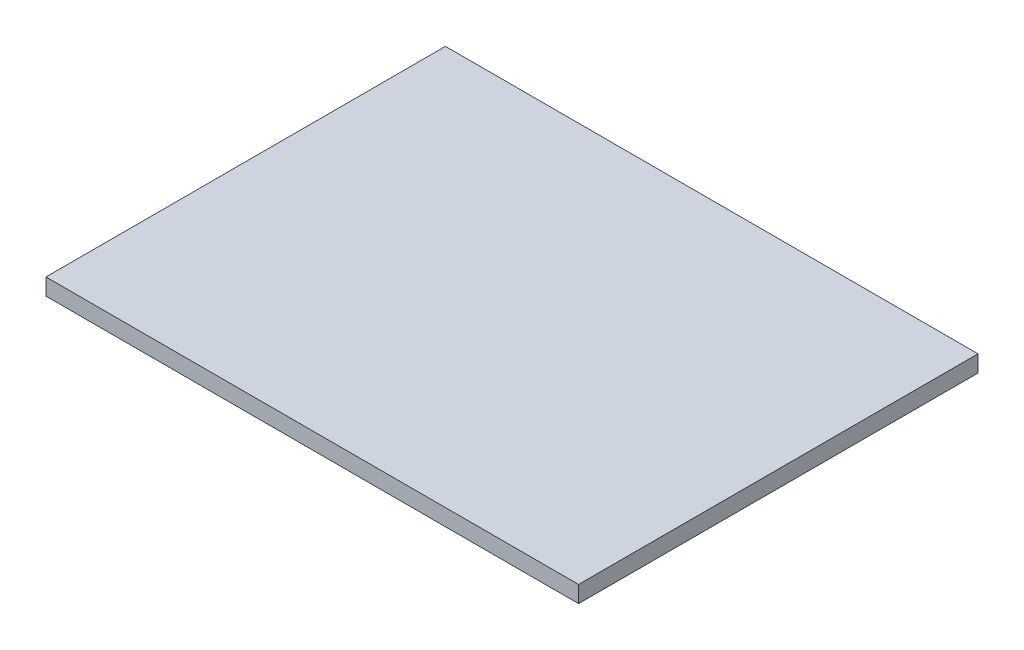
SolidWorks part; units mm, degrees
material "Brass"
ref_plane "Front Plane" through (0, 0, 0) normal (0, 0, 1) x (1, 0, 0)
ref_plane "Top Plane" through (0, 0, 0) normal (0, 1, 0) x (1, 0, 0)
ref_plane "Right Plane" through (0, 0, 0) normal (1, 0, 0) x (0, 0, -1)
sketch "Sketch1" plane through (0, 0, 0) normal (0, 1, 0) x (1, 0, 0)
  line L1 (-101.6, -76.2) -> (101.6, -76.2)
  line L2 (-101.6, -76.2) -> (-101.6, 76.2)
  line L3 (-101.6, 76.2) -> (101.6, 76.2)
  line L4 (101.6, -76.2) -> (101.6, 76.2)
  line L5 (-101.6, -76.2) -> (101.6, 76.2) construction
  line L6 (-101.6, 76.2) -> (101.6, -76.2) construction
  point P0 (0, 0)
  dimension "D1" = 203.2
  dimension "D2" = 152.4
extrude "Boss-Extrude1" add sketch "Sketch1" along normal blind 6.35
sketch "Sketch3" plane through (0, 0, 0) normal (0, -1, 0) x (1, 0, 0)
  line L0 (-85.1801, 48.2528) -> (-14.3562, 48.2528) construction
  line L1 (-85.1801, 22.8528) -> (-14.3562, 22.8528) construction
  line L2 (-85.1801, -2.5472) -> (-14.3562, -2.5472) construction
  line L3 (-85.1801, -27.9472) -> (-14.3562, -27.9472) construction
  line L4 (-85.1801, -53.3472) -> (-14.3562, -53.3472) construction
  line L5 (17.0679, 48.2528) -> (87.8918, 48.2528) construction
  text T0 "HI" font "Arial" height 12.7
  text T1 "HI" font "Arial" height 12.7
  text T2 "HI" font "Arial" height 12.7
  text T3 "HI" font "Arial" height 12.7
  text T4 "HI" font "Arial" height 12.7
  text T5 "HELLO" font "Arial" height 12.7
  dimension "D1" = 5
